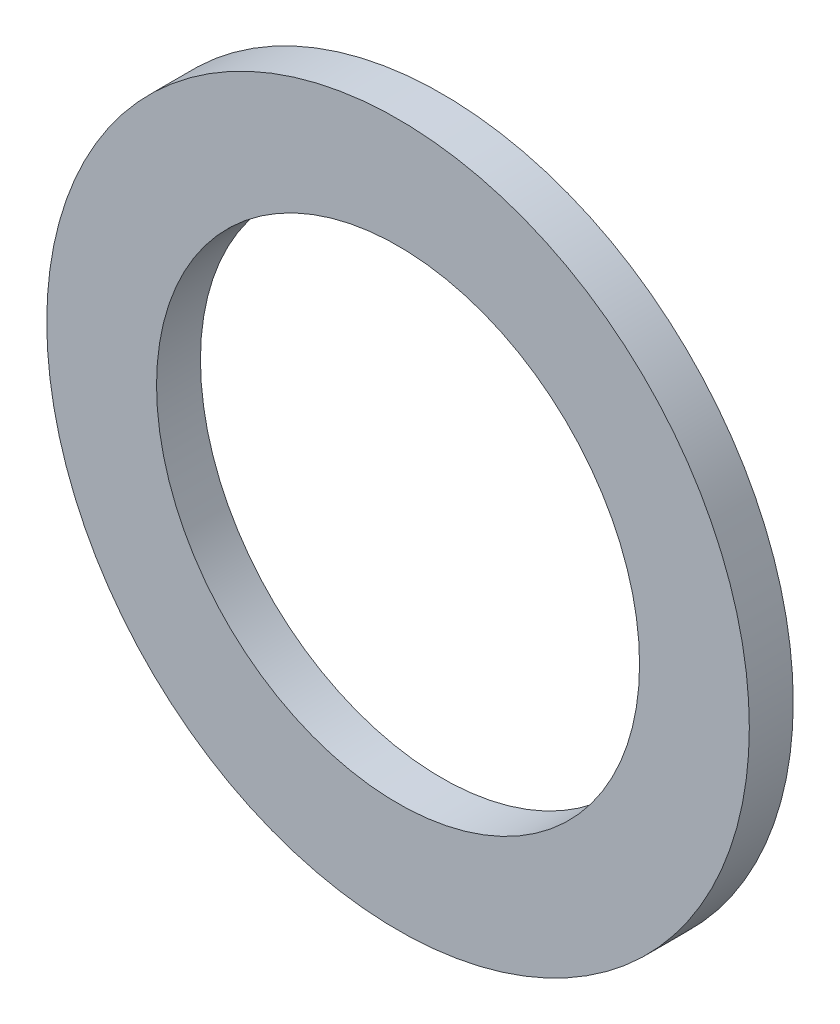
SolidWorks part; units mm, degrees
ref_plane "前视基准面" through (0, 0, 0) normal (0, 0, 1) x (1, 0, 0)
ref_plane "上视基准面" through (0, 0, 0) normal (0, 1, 0) x (1, 0, 0)
ref_plane "右视基准面" through (0, 0, 0) normal (1, 0, 0) x (0, 0, -1)
sketch "草图1" plane through (0, 0, 0) normal (0, 0, 1) x (1, 0, 0)
  circle A0 centre (0, 0) radius 5.5
  circle A1 centre (0, 0) radius 8
  dimension "D1" = 11
extrude "凸台-拉伸1" add sketch "草图1" along normal blind 1
